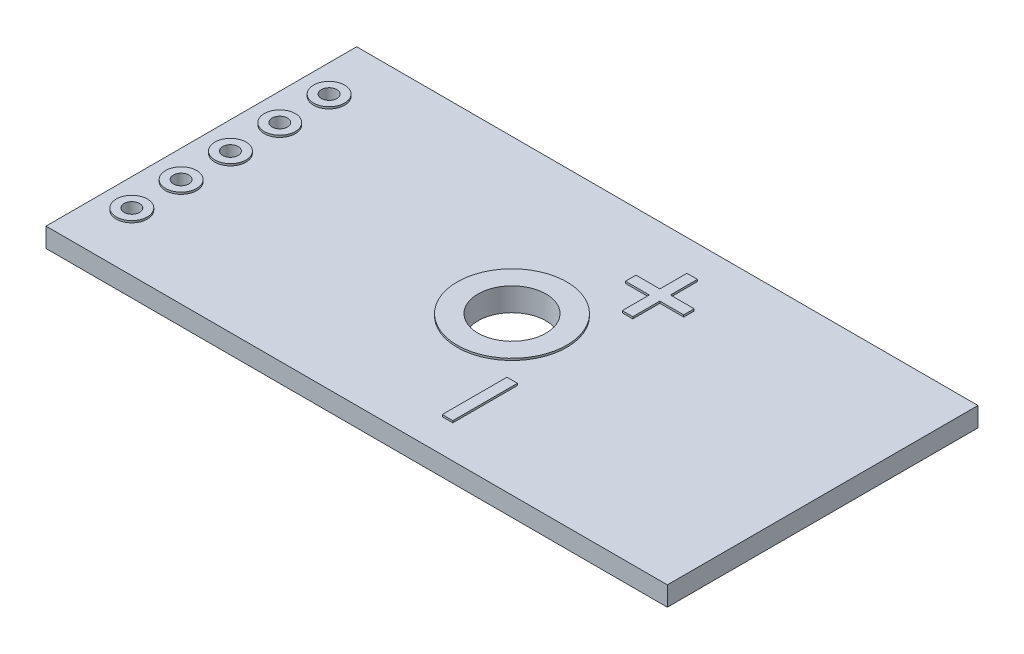
SolidWorks part; units mm, degrees
ref_plane "Front Plane" through (0, 0, 0) normal (0, 0, 1) x (1, 0, 0)
ref_plane "Top Plane" through (0, 0, 0) normal (0, 1, 0) x (1, 0, 0)
ref_plane "Right Plane" through (0, 0, 0) normal (1, 0, 0) x (0, 0, -1)
sketch "Sketch1" plane through (0, 0, 0) normal (0, 1, 0) x (1, 0, 0)
  line L1 (16, -8) -> (-16, -8)
  line L2 (16, -8) -> (16, 8)
  line L3 (16, 8) -> (-16, 8)
  line L4 (-16, -8) -> (-16, 8)
  line L5 (16, -8) -> (-16, 8) construction
  line L6 (16, 8) -> (-16, -8) construction
  point P0 (0, 0)
  dimension "D1" = 32
  dimension "D2" = 16
extrude "Boss-Extrude1" add sketch "Sketch1" along normal blind 1
sketch "Sketch2" plane through (0, 1, 0) normal (0, 1, 0) x (1, 0, 0)
  line L0 (-17.0658, 0) -> (18.7298, 0) construction
  line L9 (-14.5, 15.2965) -> (-14.5, -4.8264) construction
  circle A0 centre (0, 0) radius 1.75
  circle A2 centre (-14.5, -5.08) radius 0.4
  circle A4 centre (-14.5, -2.54) radius 0.4
  circle A6 centre (-14.5, 0) radius 0.4
  circle A7 centre (-14.5, 2.54) radius 0.4
  circle A8 centre (-14.5, 5.08) radius 0.4
  dimension "D1" = 3.5
extrude "Cut-Extrude1" cut sketch "Sketch2" against normal blind 1
sketch "Sketch3" plane through (0, 1, 0) normal (0, 1, 0) x (1, 0, 0)
  circle A0 centre (-14.5, -5.08) radius 0.4 construction
  circle A1 centre (-14.5, -2.54) radius 0.4 construction
  circle A2 centre (-14.5, 0) radius 0.4 construction
  circle A3 centre (-14.5, 2.54) radius 0.4 construction
  circle A4 centre (-14.5, 5.08) radius 0.4 construction
  circle A20 centre (-14.5, 5.08) radius 0.4
  circle A21 centre (-14.5, 2.54) radius 0.4
  circle A22 centre (-14.5, 0) radius 0.4
  circle A23 centre (-14.5, -2.54) radius 0.4
  circle A24 centre (-14.5, -5.08) radius 0.4
  circle A25 centre (-14.5, 5.08) radius 0.8
  circle A26 centre (-14.5, 2.54) radius 0.8
  circle A27 centre (-14.5, 0) radius 0.8
  circle A28 centre (-14.5, -2.54) radius 0.8
  circle A29 centre (-14.5, -5.08) radius 0.8
  circle A30 centre (0, 0) radius 2.8234
  circle A31 centre (0, 0) radius 1.75
  dimension "D1" = 1.6
extrude "Boss-Extrude2" add sketch "Sketch3" along normal blind 0.1 and the other way offset from surface (1.1 mm away) 0.1 other way up to face at (-14.5, 0, -4.68)
sketch "Sketch4" plane through (0, 1, 0) normal (0, 1, 0) x (1, 0, 0)
  line L0 (3.2506, 6.3) -> (3.2506, 4.9059)
  line L1 (2.7088, -2.9709) -> (3.2506, -2.9709)
  line L2 (2.7088, -2.9709) -> (2.7088, -6.2989)
  line L3 (2.7088, -6.2989) -> (3.2506, -6.2989)
  line L4 (3.2506, -2.9709) -> (3.2506, -6.2989)
  line L5 (2.7088, -2.9709) -> (3.2506, -6.2989) construction
  line L6 (2.7088, -6.2989) -> (3.2506, -2.9709) construction
  line L7 (3.2506, 4.9059) -> (4.4797, 4.9059)
  line L8 (4.4797, 4.9059) -> (4.4797, 4.3641)
  line L9 (4.4797, 4.3641) -> (3.2506, 4.3641)
  line L10 (3.2506, 4.3641) -> (3.2506, 2.97)
  line L11 (3.2506, 2.97) -> (2.7088, 2.97)
  line L12 (2.7088, 2.97) -> (2.7088, 4.3641)
  line L13 (2.7088, 4.3641) -> (1.4797, 4.3641)
  line L14 (1.4797, 4.3641) -> (1.4797, 4.9059)
  line L15 (1.4797, 4.9059) -> (2.7088, 4.9059)
  line L16 (2.7088, 4.9059) -> (2.7088, 6.3)
  line L17 (2.7088, 6.3) -> (3.2506, 6.3)
  line L18 (-16, -8) -> (16, -8) construction
  line L19 (16, 8) -> (-16, 8) construction
  line L20 (1.3115, 4.635) -> (4.4686, 4.635) construction
  line L21 (2.9797, 8.3798) -> (2.9797, 1.64) construction
  point P0 (2.9797, -4.6349)
  dimension "D1" = 3.328
  dimension "D2" = 3.33
  dimension "D3" = 1.7011
  dimension "D4" = 1.7
  dimension "D5" = 3
extrude "Boss-Extrude3" add sketch "Sketch4" along normal blind 0.1
